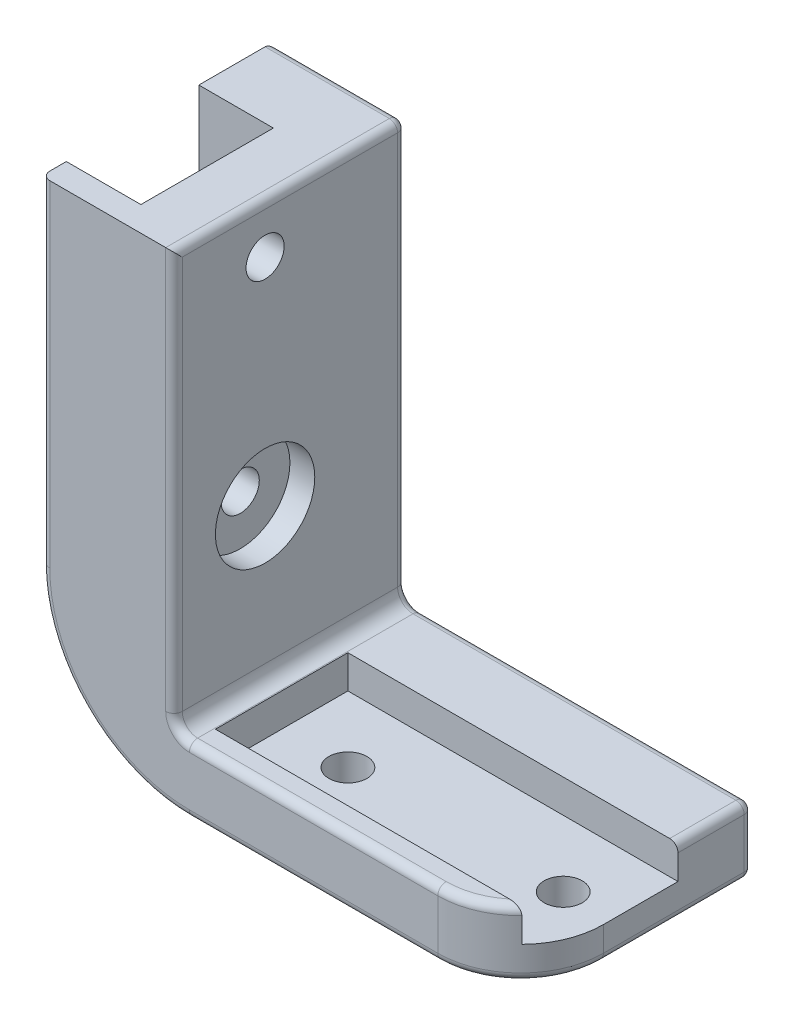
SolidWorks part; units mm, degrees
ref_plane "Front Plane" through (0, 0, 0) normal (0, 0, 1) x (1, 0, 0)
ref_plane "Top Plane" through (0, 0, 0) normal (0, 1, 0) x (1, 0, 0)
ref_plane "Right Plane" through (0, 0, 0) normal (1, 0, 0) x (0, 0, -1)
sketch "Sketch2" plane through (0, 0, 0) normal (0, 0, 1) x (1, 0, 0)
  line L0 (-0.745, -5.9434) -> (19.255, -5.9434)
  line L1 (-1.6746, 23.241) -> (-1.6746, -1.0138)
  line L2 (19.255, -1.9434) -> (-0.745, -1.9434)
  line L4 (19.255, -1.9434) -> (19.255, -5.9434)
  line L5 (-9.6746, 2.9862) -> (19.255, -5.9434) construction
  line L6 (-8.5859, 0.8665) -> (19.255, -1.9434) construction
  line L8 (-9.6746, 2.9862) -> (-9.6746, 23.241)
  line L9 (-9.6746, 23.241) -> (-1.6746, 23.241)
  arc A0 (-9.6746, 2.9862) -> (-0.745, -5.9434) centre (-0.745, 2.9862) ccw
  arc A1 (-1.6746, -1.0138) -> (-0.745, -1.9434) centre (-0.745, -1.0138) ccw
  point P0 (0, 0)
  dimension "D1" = 4
  dimension "D2" = 20
  dimension "D3" = 8
  dimension "D7" = 20
extrude "Boss-Extrude2" add sketch "Sketch2" along normal blind 14
sketch "Sketch3" plane through (-1.6746, 0, 0) normal (1, 0, 0) x (0, 0, -1)
  line L0 (-14, -1.0138) -> (-14, 23.241) construction
  line L1 (-14, 23.241) -> (0, 23.241) construction
  circle A0 centre (-8.5, 20.241) radius 1.15
  circle A1 centre (-8.5, 7.241) radius 1.15
  dimension "D1" = 2.3
  dimension "D2" = 2.3
  dimension "D3" = 5.5
  dimension "D4" = 5.5
  dimension "D7" = 13
  dimension "D5" = 3
  dimension "D6" = 16
extrude "Cut-Extrude1" cut sketch "Sketch3" against normal through all and the other way blind 6
sketch "Sketch4" plane through (0, -1.9434, 0) normal (0, 1, 0) x (1, 0, 0)
  line L0 (19.255, -14) -> (-0.745, -14) construction
  line L1 (-1.6746, -14) -> (-1.6746, 0) construction
  circle A0 centre (3.3254, -8.5) radius 1.15
  circle A1 centre (16.3254, -8.5) radius 1.15
  dimension "D1" = 2.3
  dimension "D2" = 2.3
  dimension "D3" = 5.5
  dimension "D4" = 5.5
  dimension "D6" = 13
  dimension "D5" = 5
extrude "Cut-Extrude2" cut sketch "Sketch4" against normal through all
sketch "Sketch5" plane through (0, -1.9434, 0) normal (0, 1, 0) x (1, 0, 0)
  line L0 (19.255, -14) -> (14.255, -14)
  line L1 (19.255, -14) -> (-0.745, -14) construction
  line L2 (19.255, -9) -> (19.255, -14)
  arc A0 (14.255, -14) -> (19.255, -9) centre (14.255, -9) ccw
  dimension "D1" = 5
  dimension "D2" = 5
extrude "Cut-Extrude3" cut sketch "Sketch5" against normal through all
sketch "Sketch6" plane through (0, -1.9434, 0) normal (0, 1, 0) x (1, 0, 0)
  line L0 (-0.745, -14) -> (-0.745, 0) construction
  line L1 (21.3254, -4.5) -> (-0.6746, -4.5)
  line L2 (21.3254, -4.5) -> (21.3254, -12.5)
  line L3 (21.3254, -12.5) -> (-0.6746, -12.5)
  line L4 (-0.6746, -4.5) -> (-0.6746, -12.5)
  circle A0 centre (16.3254, -8.5) radius 1.15 construction
  circle A2 centre (3.3254, -8.5) radius 1.15 construction
  dimension "D1" = 4
  dimension "D2" = 4
  dimension "D3" = 22
  dimension "D4" = 5
  dimension "D5" = 4
  dimension "D6" = 0.0704
extrude "Cut-Extrude4" cut sketch "Sketch6" against normal blind 2
sketch "Sketch7" plane through (-9.6746, 0, 0) normal (-1, 0, 0) x (0, 0, 1)
  line L0 (4.5, 3.6337) -> (12.5, 3.6337)
  line L1 (12.5, 3.6337) -> (12.5, 24.6337)
  line L2 (4.5, 24.6337) -> (12.5, 24.6337)
  line L4 (4.5, 24.6337) -> (4.5, 3.6337)
  circle A0 centre (8.5, 7.241) radius 1.15 construction
  dimension "D3" = 4
  dimension "D1" = 21
  dimension "D2" = 4
  dimension "D4" = 21
extrude "Cut-Extrude5" cut sketch "Sketch7" against normal blind 4.5
fillet "Fillet3" radius 0.5 19 edges at (-7.0591, -3.328, 0) (-9.6746, 13.1136, 0) (-5.6746, 23.241, 0) (19.255, -3.9434, 0) (-9.6746, 13.1136, 14) (-7.0591, -3.328, 14) (-1.6746, 11.1136, 14) (-1.6746, 23.241, 7) (-1.6746, 11.1136, 0) (-1.4023, -1.6711, 0) (9.255, -1.9434, 0) (19.255, -1.9434, 2.25) (16.1915, -1.9434, 13.6098) (6.755, -1.9434, 14) (-1.4023, -1.6711, 14) (9.255, -5.9434, 0) (19.255, -5.9434, 4.5) (17.7905, -5.9434, 12.5355) (6.755, -5.9434, 14)
sketch "Sketch8" plane through (-1.6746, 0, 0) normal (1, 0, 0) x (0, 0, -1)
  circle A1 centre (-8.5, 7.241) radius 3
  dimension "D1" = 6
extrude "Cut-Extrude7" cut sketch "Sketch8" against normal blind 1.5
